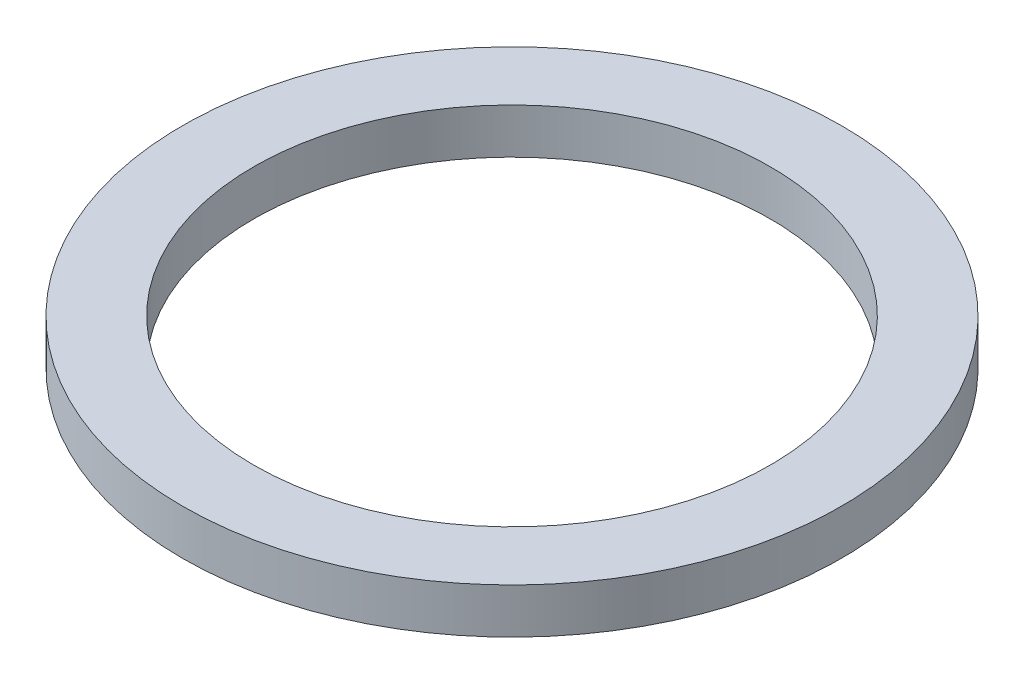
SolidWorks part; units mm, degrees
ref_plane "Front Plane" through (0, 0, 0) normal (0, 0, 1) x (1, 0, 0)
ref_plane "Top Plane" through (0, 0, 0) normal (0, 1, 0) x (1, 0, 0)
ref_plane "Right Plane" through (0, 0, 0) normal (1, 0, 0) x (0, 0, -1)
sketch "Sketch1" plane through (0, 0, 0) normal (0, 1, 0) x (1, 0, 0)
  circle A0 centre (0, 0) radius 17.15
  circle A1 centre (0, 0) radius 21.875
  dimension "D1" = 34.3
  dimension "D2" = 43.75
extrude "Boss-Extrude1" add sketch "Sketch1" along normal blind 3
